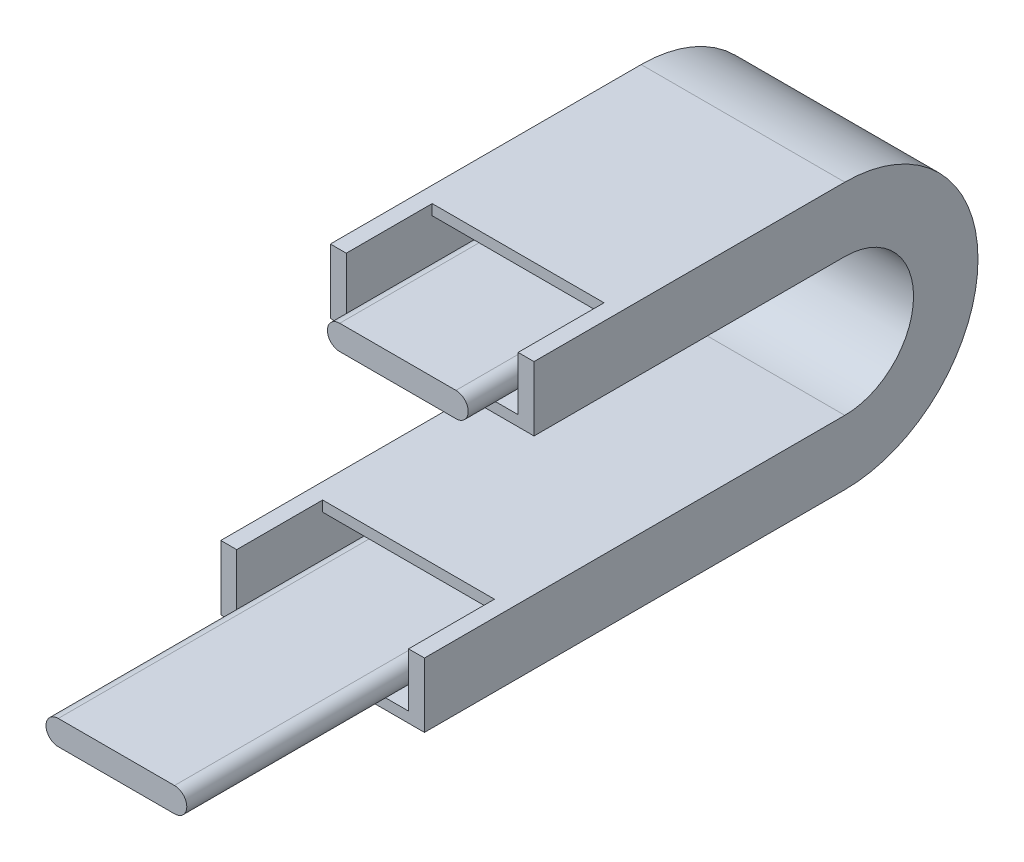
SolidWorks part; units mm, degrees
material "Nylon 6/10"
ref_plane "Front" through (0, 0, 0) normal (0, 0, 1) x (1, 0, 0)
ref_plane "Top" through (0, 0, 0) normal (0, 1, 0) x (1, 0, 0)
ref_plane "Right" through (0, 0, 0) normal (1, 0, 0) x (0, 0, -1)
sketch "Sketch15" plane through (0, 0, 0) normal (1, 0, 0) x (0, 0, -1)
  line L0 (75.8363, 0) -> (0, 0)
  line L1 (75.8363, 47) -> (25.5, 47)
  line L2 (55.8363, 47) -> (55.8363, 37.6216) construction
  arc A0 (75.8363, 0) -> (75.8363, 47) centre (75.8363, 23.5) ccw
  dimension "PathLength" = 200
  dimension "LINK PITCH" = 20
  dimension "PITCH DIAMETER" = 47
  dimension "MOVING LINK OFFSET" = 25.5
ref_plane "Plane2" through (0, 0, 0) normal (0, 0, 1) x (1, 0, 0)
sketch "Sketch2" plane through (0, 0, 0) normal (0, 0, 1) x (1, 0, 0)
  line L0 (-23.7, 7.5) -> (23.7, -7.5) construction
  line L1 (-23.7, 7.5) -> (23.7, 7.5)
  line L2 (-23.7, 7.5) -> (-23.7, -7.5)
  line L3 (-23.7, -7.5) -> (23.7, -7.5)
  line L4 (23.7, 7.5) -> (23.7, -7.5)
  line L7 (-20, 5.05) -> (-20, -5.05)
  line L9 (20, 5.05) -> (20, -5.05)
  line L18 (-20, 5.05) -> (20, 5.05)
  line L19 (-20, -5.05) -> (20, -5.05)
  line L29 (-23.7, 0) -> (-20, 0) construction
  line L31 (20, 0) -> (23.7, 0) construction
  dimension "D1" = 15
  dimension "D2" = 47.4
  dimension "D3" = 40
  dimension "D4" = 10.1
sweep "Sweep1" add profiles "Sketch2" path "Sketch15"
sketch "Sketch1" plane through (0, 0, 0) normal (0, 0, 1) x (1, 0, 0)
  line L0 (-13.5255, -2.1425) -> (13.5255, -2.1425) construction
  line L1 (-13.5255, 0.715) -> (13.5255, 0.715)
  line L2 (-20, -5.05) -> (20, -5.05) construction
  line L3 (0, -2.1425) -> (0, 0) construction
  line L4 (-13.5255, -5) -> (13.5255, -5)
  arc A0 (-13.5255, 0.715) -> (-13.5255, -5) centre (-13.5255, -2.1425) ccw
  arc A1 (13.5255, -5) -> (13.5255, 0.715) centre (13.5255, -2.1425) ccw
  dimension "D1" = 5.715
  dimension "D2" = 32.766
  dimension "D3" = 0.05
ref_plane "Plane5" through (0, 0, -6.46) normal (0, 0, 1) x (1, 0, 0)
sketch "Sketch26" plane through (23.7, 0, 0) normal (1, 0, 0) x (0, 0, -1)
  line L0 (25.5, 54.5) -> (25.5, 39.5) construction
  line L1 (25.5, 39.5) -> (3.5, 39.5)
  line L2 (25.5, 54.5) -> (3.5, 54.5)
  line L3 (3.5, 54.5) -> (3.5, 39.5)
  line L4 (25.5, 54.5) -> (25.5, 39.5)
  line L5 (0, -7.5) -> (0, 7.5) construction
  line L6 (0, -7.5) -> (-22, -7.5)
  line L7 (0, 7.5) -> (-22, 7.5)
  line L8 (-22, 7.5) -> (-22, -7.5)
  line L9 (0, -7.5) -> (0, 7.5)
  dimension "D1" = 22
extrude "Extrude7" add sketch "Sketch26" against normal up to surface (47.4 mm away) up to face at (-23.7, 23.5, -50.1681)
sketch "Sketch30" plane through (0, 0, 0) normal (1, 0, 0) x (0, 0, -1)
  line L0 (75.8363, 0) -> (0, 0) construction
  line L1 (75.8363, 47) -> (25.5, 47) construction
  line L2 (75.8363, 0) -> (-22, 0)
  line L3 (75.8363, 47) -> (3.5, 47)
  line L4 (3.5, 54.5) -> (3.5, 39.5) construction
  line L5 (-22, 7.5) -> (-22, -7.5) construction
  arc A0 (75.8363, 0) -> (75.8363, 47) centre (75.8363, 23.5) ccw construction
  arc A1 (75.8363, 0) -> (75.8363, 47) centre (75.8363, 23.5) ccw
ref_plane "Plane4" through (0, 0, 22) normal (0, 0, 1) x (1, 0, 0)
sketch "Sketch29" plane through (0, 0, 22) normal (0, 0, 1) x (1, 0, 0)
  line L0 (-20, 5.05) -> (-20, -5.05) construction
  line L1 (-20, -5.05) -> (20, -5.05) construction
  line L2 (-20, 5.05) -> (20, 5.05) construction
  line L3 (20, 5.05) -> (20, -5.05) construction
  line L4 (-20, 5.05) -> (-20, -5.05)
  line L5 (-20, -5.05) -> (20, -5.05)
  line L6 (-20, 5.05) -> (20, 5.05)
  line L7 (20, 5.05) -> (20, -5.05)
sweep "Cut-Sweep2" cut profiles "Sketch29" path "Sketch30"
sketch "Sketch34" plane through (0, 0, 0) normal (1, 0, 0) x (0, 0, -1)
  line L0 (75.8363, 21.3075) -> (75.8363, 23.5) construction
  line L1 (75.8363, -2.1925) -> (0, -2.1925)
  line L2 (75.8363, -5.05) -> (-22, -5.05) construction
  line L3 (75.8363, 44.8075) -> (25.5, 44.8075)
  arc A0 (75.8363, -2.1925) -> (75.8363, 44.8075) centre (75.8363, 21.3075) ccw
  arc A1 (75.8363, 0) -> (75.8363, 47) centre (75.8363, 23.5) ccw construction
  dimension "D1" = 2.8575
sketch "Sketch35" plane through (0, 54.5, 0) normal (0, 1, 0) x (1, 0, 0)
  line L0 (-23.7, 3.5) -> (23.7, 3.5) construction
  line L1 (-20, 3.5) -> (20, 3.5)
  line L2 (-20, 3.5) -> (-20, 23.5)
  line L3 (-20, 23.5) -> (20, 23.5)
  line L4 (20, 3.5) -> (20, 23.5)
  line L5 (0, 100.7735) -> (0, 40.7499) construction
  point P8 (0, 3.5)
  point P9 (0, 23.5)
  dimension "D1" = 40
  dimension "D2" = 20
extrude "Cut-Extrude1" cut sketch "Sketch35" against normal up to next
sketch "Sketch36" plane through (0, 7.5, 0) normal (0, 1, 0) x (1, 0, 0)
  line L0 (-23.7, -22) -> (23.7, -22) construction
  line L1 (-20, -22) -> (20, -22)
  line L2 (-20, -22) -> (-20, -2)
  line L3 (-20, -2) -> (20, -2)
  line L4 (20, -22) -> (20, -2)
  line L5 (0, -34.1) -> (0, 34.1) construction
  point P6 (0, -2)
  dimension "D1" = 40
  dimension "D2" = 20
extrude "Cut-Extrude2" cut sketch "Sketch36" against normal up to next
sweep "Sweep2" add profiles "Sketch1" path "Sketch34"
ref_plane "Plane3" through (0, 0, 190) normal (0, 0, 1) x (1, 0, 0)
sketch "Sketch25" plane through (0, 0, 0) normal (0, 0, 1) x (1, 0, 0)
  line L0 (13.5255, 0.715) -> (-13.5255, 0.715) construction
  line L1 (13.5255, 0.715) -> (-13.5255, 0.715)
  line L2 (-13.5255, -5) -> (13.5255, -5) construction
  line L3 (-13.5255, -5) -> (13.5255, -5)
  arc A0 (-13.5255, 0.715) -> (-13.5255, -5) centre (-13.5255, -2.1425) ccw construction
  arc A1 (13.5255, -5) -> (13.5255, 0.715) centre (13.5255, -2.1425) ccw construction
  arc A2 (-13.5255, 0.715) -> (-13.5255, -5) centre (-13.5255, -2.1425) ccw
  arc A4 (13.5255, -5) -> (13.5255, 0.715) centre (13.5255, -2.1425) ccw
extrude "Extrude4" add sketch "Sketch25" along normal offset from surface (70 mm away) 70 up to plane "Front"
sketch "Sketch31" plane through (0, 0, -25.5) normal (0, 0, 1) x (1, 0, 0)
  line L2 (-13.5255, 41.9) -> (13.5255, 41.9)
  line L3 (-13.5255, 41.9) -> (13.5255, 41.9)
  line L4 (13.5255, 47.615) -> (-13.5255, 47.615)
  line L5 (13.5255, 47.615) -> (-13.5255, 47.615)
  arc A1 (-13.5255, 47.615) -> (-13.5255, 41.9) centre (-13.5255, 44.7575) ccw
  arc A2 (-13.5255, 47.615) -> (-13.5255, 41.9) centre (-13.5255, 44.7575) ccw
  arc A6 (13.5255, 41.9) -> (13.5255, 47.615) centre (13.5255, 44.7575) ccw
  arc A7 (13.5255, 41.9) -> (13.5255, 47.615) centre (13.5255, 44.7575) ccw
  dimension "D1" = 0
extrude "Extrude8" add sketch "Sketch31" along normal blind 30
equation "\"D1@Sketch3\" = \"QUARTER TRAVEL@Sketch3\""
